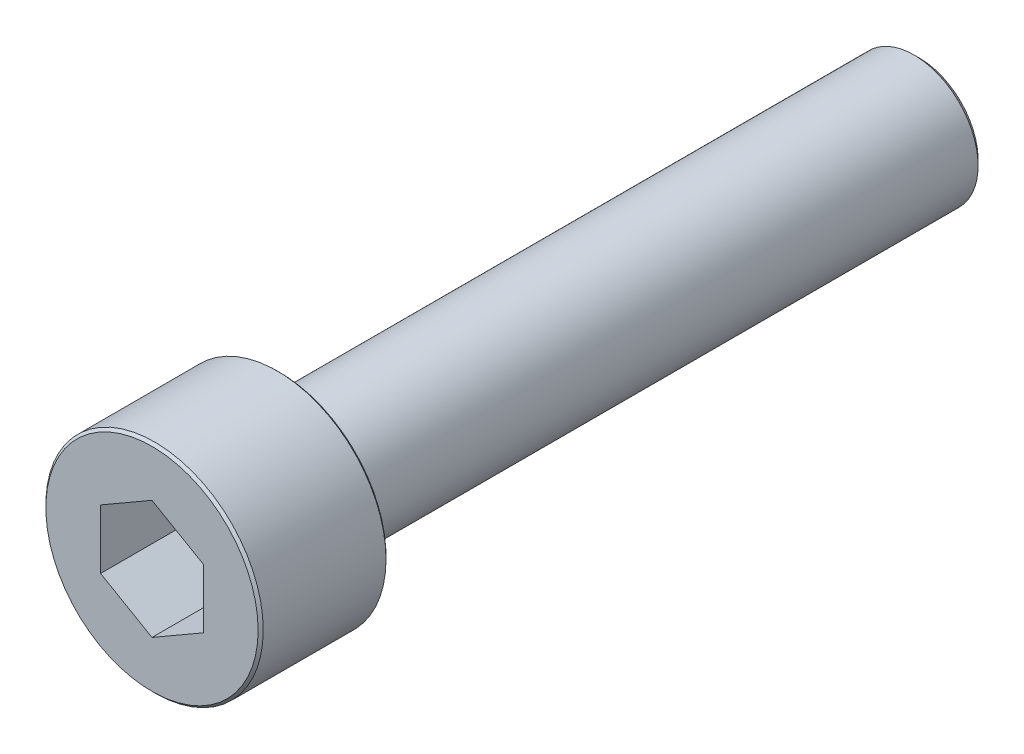
SolidWorks part; units mm, degrees
ref_plane "前视基准面" through (0, 0, 0) normal (0, 0, 1) x (1, 0, 0)
ref_plane "上视基准面" through (0, 0, 0) normal (0, 1, 0) x (1, 0, 0)
ref_plane "右视基准面" through (0, 0, 0) normal (1, 0, 0) x (0, 0, -1)
other "Configuration Table"
sketch "草图1" plane through (0, 0, 0) normal (0, 1, 0) x (1, 0, 0)
  line L0 (4.25, -25) -> (0, -25)
  line L1 (0, -25) -> (0, -30)
  line L2 (0, -30) -> (4.25, -30)
  line L3 (4.25, -30) -> (4.25, -25)
  line L4 (0, -25) -> (0, -30) construction
revolve "旋转1" add sketch "草图1" angle 360 about L4
sketch "草图2" plane through (0, 0, 25) normal (0, 0, -1) x (-1, 0, 0)
  circle A0 centre (0, 0) radius 2.5
extrude "凸台-拉伸1" add sketch "草图2" along normal blind 25
sketch "草图3" plane through (0, 0, 30) normal (0, 0, 1) x (1, 0, 0)
  line L0 (-2.01, -1.1605) -> (0, -2.3209)
  line L1 (0, -2.3209) -> (2.01, -1.1605)
  line L2 (2.01, -1.1605) -> (2.01, 1.1605)
  line L3 (2.01, 1.1605) -> (0, 2.3209)
  line L4 (0, 2.3209) -> (-2.01, 1.1605)
  line L5 (-2.01, 1.1605) -> (-2.01, -1.1605)
extrude "切除-拉伸1" cut sketch "草图3" against normal blind 3.75
chamfer "倒角1" distance 0.1 angle 45 2 edges at (4.25, 0, 25) (4.25, 0, 30)
chamfer "倒角2" distance 0.2 angle 45 1 edges at (-2.5, 0, 0)
